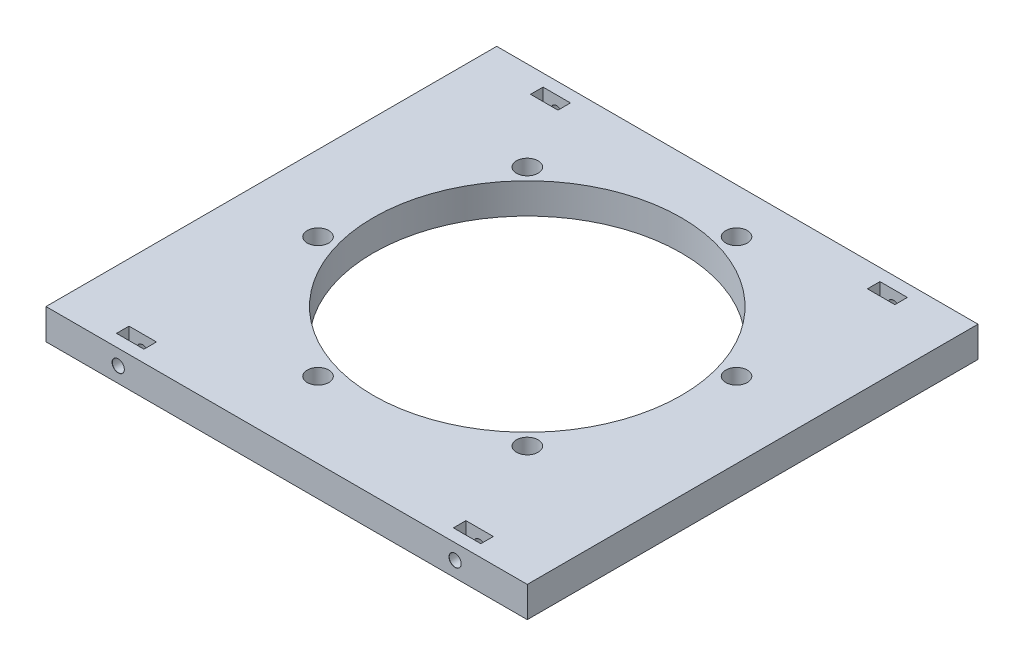
SolidWorks part; units mm, degrees
material "6061 Alloy"
ref_plane "Front Plane" through (0, 0, 0) normal (0, 0, 1) x (1, 0, 0)
ref_plane "Top Plane" through (0, 0, 0) normal (0, 1, 0) x (1, 0, 0)
ref_plane "Right Plane" through (0, 0, 0) normal (1, 0, 0) x (0, 0, -1)
sketch "Sketch1" plane through (0, 0, 0) normal (0, 1, 0) x (1, 0, 0)
  line L1 (-50, -50) -> (50, -50)
  line L2 (-50, -50) -> (-50, 50)
  line L3 (-50, 50) -> (50, 50)
  line L4 (50, -50) -> (50, 50)
  line L5 (-50, -50) -> (50, 50) construction
  line L6 (-50, 50) -> (50, -50) construction
  circle A1 centre (0, 0) radius 39.5
  arc A5 (-25.1023, 25.1023) -> (9.1881, 34.2904) centre (0, 0) cw
  arc A7 (9.1881, 34.2904) -> (-34.2904, -9.1881) centre (0, 0) ccw
  arc A9 (-34.2904, -9.1881) -> (-9.1881, -34.2904) centre (0, 0) ccw
  arc A11 (-9.1881, -34.2904) -> (25.1023, -25.1023) centre (0, 0) ccw
  circle A13 centre (0, 0) radius 32
  arc A14 (25.1023, -25.1023) -> (34.2904, 9.1881) centre (0, 0) ccw
extrude "Boss-Extrude3" add sketch "Sketch1" along normal blind 6.35
hole_wizard "M4 Clearance Hole2" positions "Sketch6" profile "Sketch7" hole size "M4" standard "ANSI Metric" end condition through all
sketch "Sketch6" plane through (0, 0, 0) normal (0, -1, 0) x (-1, 0, 0)
  point P0 (-9.1881, 34.2904)
  point P3 (25.1023, 25.1023)
  point P6 (34.2904, -9.1881)
  point P9 (9.1881, -34.2904)
  point P12 (-25.1023, -25.1023)
  point P15 (-34.2904, 9.1881)
sketch "Sketch7" plane through (9.1881, 0, -34.2904) normal (1, 0, 0) x (0, 0, -1)
  line L0 (0, 0) -> (0, 6.35)
  line L1 (0, 6.35) -> (2.25, 6.35)
  line L2 (2.25, 6.35) -> (2.25, 0.025)
  line L3 (2.25, 0.025) -> (2.275, 0)
  line L5 (2.275, 0) -> (0, 0)
  line L6 (-2.25, 0.025) -> (-2.275, 0) construction
  line L11 (0, -6.35) -> (0, 107.95) construction
  dimension "Thru Hole Dia." = 4.5
  dimension "Thru Hole Depth" = 6.35
  dimension "Near C'Sink Dia." = 4.55
  dimension "Near C'Sink Angle" = 90
sketch "Sketch13" plane through (0, 6.35, 0) normal (0, 1, 0) x (1, 0, 0)
  line L0 (-50, -50) -> (-46.1091, -46.1091)
  line L1 (-46.1091, -46.1091) -> (-68.3017, -23.9166)
  line L2 (-46.1091, -46.1091) -> (-23.9166, -68.3017)
sketch "Sketch16" plane through (0, 6.35, 0) normal (0, 1, 0) x (1, 0, 0)
  line L0 (-50, -50) -> (-55, -50)
  line L1 (-50, -50) -> (50, -50) construction
  line L2 (-55, -50) -> (-55, -70)
  line L3 (-50, -50) -> (-75, -50)
  line L4 (-75, -50) -> (-75, -70)
  line L5 (-75, -70) -> (-55, -70)
  line L6 (-50, 50) -> (-55, 50)
  line L7 (-50, 50) -> (50, 50) construction
  line L8 (50, 50) -> (55, 50)
  line L9 (50, -50) -> (55, -50)
  line L11 (-55, 50) -> (-75, 50)
  line L12 (-55, 50) -> (-55, 70)
  line L13 (-55, 70) -> (-75, 70)
  line L14 (-75, 50) -> (-75, 70)
  line L15 (55, 50) -> (75, 50)
  line L16 (55, 50) -> (55, 70)
  line L17 (55, 70) -> (75, 70)
  line L18 (75, 50) -> (75, 70)
  line L19 (55, -50) -> (75, -50)
  line L20 (55, -50) -> (55, -70)
  line L21 (55, -70) -> (75, -70)
  line L22 (75, -50) -> (75, -70)
sketch "Sketch23" plane through (0, 6.35, 0) normal (0, 1, 0) x (1, 0, 0)
  line L0 (-50, -50) -> (-50, -55)
  line L1 (-50, -50) -> (-50, 50) construction
  line L2 (-50, 50) -> (-50, 55)
  line L3 (85, 50) -> (50, 55)
  line L4 (-50, 50) -> (50, 50) construction
  line L5 (50, -50) -> (50, 50) construction
  line L6 (50, -50) -> (50, -55)
  line L8 (-50, 55) -> (-70, 55)
  line L9 (-50, 55) -> (-50, 75)
  line L10 (-50, 75) -> (-70, 75)
  line L11 (-70, 55) -> (-70, 75)
  line L12 (50, 55) -> (70, 55)
  line L13 (50, 55) -> (50, 75)
  line L14 (50, 75) -> (70, 75)
  line L15 (70, 55) -> (70, 75)
  line L16 (50, -55) -> (70, -55)
  line L17 (50, -55) -> (50, -75)
  line L18 (50, -75) -> (70, -75)
  line L19 (70, -55) -> (70, -75)
  line L20 (-50, -55) -> (-70, -55)
  line L21 (-50, -55) -> (-50, -75)
  line L22 (-50, -75) -> (-70, -75)
  line L23 (-70, -55) -> (-70, -75)
sketch "Sketch24" plane through (0, 0, 50) normal (0, 0, 1) x (1, 0, 0)
  line L0 (-50, 3.175) -> (-35, 3.175)
  line L1 (-50, 6.35) -> (-50, 0) construction
  line L2 (50, 3.175) -> (35, 3.175)
  line L3 (50, 6.35) -> (50, 0) construction
hole_wizard "Tap Drill for M3x0.5 Tap2" positions "Sketch27" profile "Sketch28" hole size "M3x0.5" standard "ANSI Metric"
sketch "Sketch27" plane through (0, 0, 50) normal (0, 0, 1) x (1, 0, 0)
  point P0 (-35, 3.175)
  point P3 (35, 3.175)
sketch "Sketch28" plane through (-35, 3.175, 50) normal (1, 0, 0) x (0, -1, 0)
  line L0 (0, 0) -> (0, 10)
  line L1 (0, 10) -> (1.25, 9.2489)
  line L2 (1.25, 9.2489) -> (1.25, 0.025)
  line L3 (1.25, 0.025) -> (1.275, 0)
  line L5 (1.275, 0) -> (0, 0)
  line L6 (-1.25, 0.025) -> (-1.275, 0) construction
  line L10 (0, 10) -> (-1.25, 9.2489) construction
  line L11 (0, -6.35) -> (0, 107.95) construction
  dimension "Hole Dia." = 2.5
  dimension "Hole Depth" = 10
  dimension "Near C'Sink Dia." = 2.55
  dimension "Near C'Sink Angle" = 90
  dimension "Drill Angle" = 118
sketch "Sketch29" plane through (0, 0, -50) normal (0, 0, -1) x (-1, 0, 0)
  line L0 (-50, 3.175) -> (-35, 3.175)
  line L1 (50, 3.175) -> (35, 3.175)
sketch "Sketch32" plane through (0, 6.35, 0) normal (0, 1, 0) x (1, 0, 0)
  line L0 (50, -50) -> (50, 50) construction
  line L1 (-50, 50) -> (50, 50)
  line L2 (-50, 50) -> (-50, 43.65)
  line L3 (-50, 43.65) -> (50, 43.65)
  line L4 (50, 50) -> (50, 43.65)
extrude "Cut-Extrude1" cut sketch "Sketch32" against normal blind 10
sketch "Sketch33" plane through (0, 0, -43.65) normal (0, 0, -1) x (-1, 0, 0)
  line L0 (-50, 3.175) -> (-35, 3.175)
  line L1 (-50, 0) -> (-50, 6.35) construction
  line L2 (50, 3.175) -> (35, 3.175)
  line L3 (50, 0) -> (50, 6.35) construction
hole_wizard "Tap Drill for M3x0.5 Tap4" positions "Sketch34" profile "Sketch35" hole size "M3x0.5" standard "ANSI Metric"
sketch "Sketch34" plane through (0, 0, -43.65) normal (0, 0, -1) x (-1, 0, 0)
  point P0 (-35, 3.175)
  point P3 (35, 3.175)
sketch "Sketch35" plane through (35, 3.175, -43.65) normal (1, 0, 0) x (0, 1, 0)
  line L0 (0, 0) -> (0, 10)
  line L1 (0, 10) -> (1.25, 9.2489)
  line L2 (1.25, 9.2489) -> (1.25, 0.025)
  line L3 (1.25, 0.025) -> (1.275, 0)
  line L5 (1.275, 0) -> (0, 0)
  line L6 (-1.25, 0.025) -> (-1.275, 0) construction
  line L10 (0, 10) -> (-1.25, 9.2489) construction
  line L11 (0, -6.35) -> (0, 107.95) construction
  dimension "Hole Dia." = 2.5
  dimension "Hole Depth" = 10
  dimension "Near C'Sink Dia." = 2.55
  dimension "Near C'Sink Angle" = 90
  dimension "Drill Angle" = 118
sketch "Sketch36" plane through (0, 6.35, 0) normal (0, 1, 0) x (1, 0, 0)
  line L0 (-50, -50) -> (50, -50) construction
  line L1 (-37.85, -47.5) -> (-32.15, -47.5)
  line L2 (-37.85, -47.5) -> (-37.85, -44.9)
  line L3 (-37.85, -44.9) -> (-32.15, -44.9)
  line L4 (-32.15, -47.5) -> (-32.15, -44.9)
  line L5 (-37.85, -47.5) -> (-32.15, -44.9) construction
  line L6 (-37.85, -44.9) -> (-32.15, -47.5) construction
  line L7 (32.15, -47.5) -> (37.85, -47.5)
  line L8 (32.15, -47.5) -> (32.15, -44.9)
  line L9 (32.15, -44.9) -> (37.85, -44.9)
  line L10 (37.85, -47.5) -> (37.85, -44.9)
  line L11 (32.15, -47.5) -> (37.85, -44.9) construction
  line L12 (32.15, -44.9) -> (37.85, -47.5) construction
  line L13 (33.75, 43.625) -> (36.25, 43.625) construction
  line L14 (-36.25, 43.625) -> (-33.75, 43.625) construction
  line L15 (33.75, 43.625) -> (36.25, 43.625) construction
  line L16 (-36.25, 43.625) -> (-33.75, 43.625) construction
  line L17 (-36.275, -50) -> (-33.725, -50) construction
  line L18 (-36.275, -50) -> (-33.725, -50) construction
  line L19 (36.25, -49.975) -> (33.75, -49.975) construction
  line L20 (36.25, -49.975) -> (33.75, -49.975) construction
  line L22 (37.85, 41.125) -> (32.15, 41.125)
  line L23 (37.85, 41.125) -> (37.85, 38.525)
  line L24 (37.85, 38.525) -> (32.15, 38.525)
  line L25 (32.15, 41.125) -> (32.15, 38.525)
  line L26 (37.85, 41.125) -> (32.15, 38.525) construction
  line L27 (37.85, 38.525) -> (32.15, 41.125) construction
  line L28 (-32.15, 38.525) -> (-37.85, 38.525)
  line L29 (-32.15, 38.525) -> (-32.15, 41.125)
  line L30 (-32.15, 41.125) -> (-37.85, 41.125)
  line L31 (-37.85, 38.525) -> (-37.85, 41.125)
  line L32 (-32.15, 38.525) -> (-37.85, 41.125) construction
  line L33 (-32.15, 41.125) -> (-37.85, 38.525) construction
  point P0 (-35, -46.2)
  point P5 (35, -46.2)
  point P12 (-35, 39.825)
  point P14 (-35, -50)
  point P17 (35, -49.975)
  point P25 (35, 39.825)
  point P32 (0, 0)
  point P33 (-35, 43.625)
  point P34 (0, 0)
  point P35 (35, 43.625)
  point P36 (0, 0)
  point P37 (0, 0)
  dimension "D1" = 2.5
  dimension "D2" = 2.6
  dimension "D3" = 5.7
  dimension "D4" = 2.5
extrude "Cut-Extrude2" cut sketch "Sketch36" against normal through all
